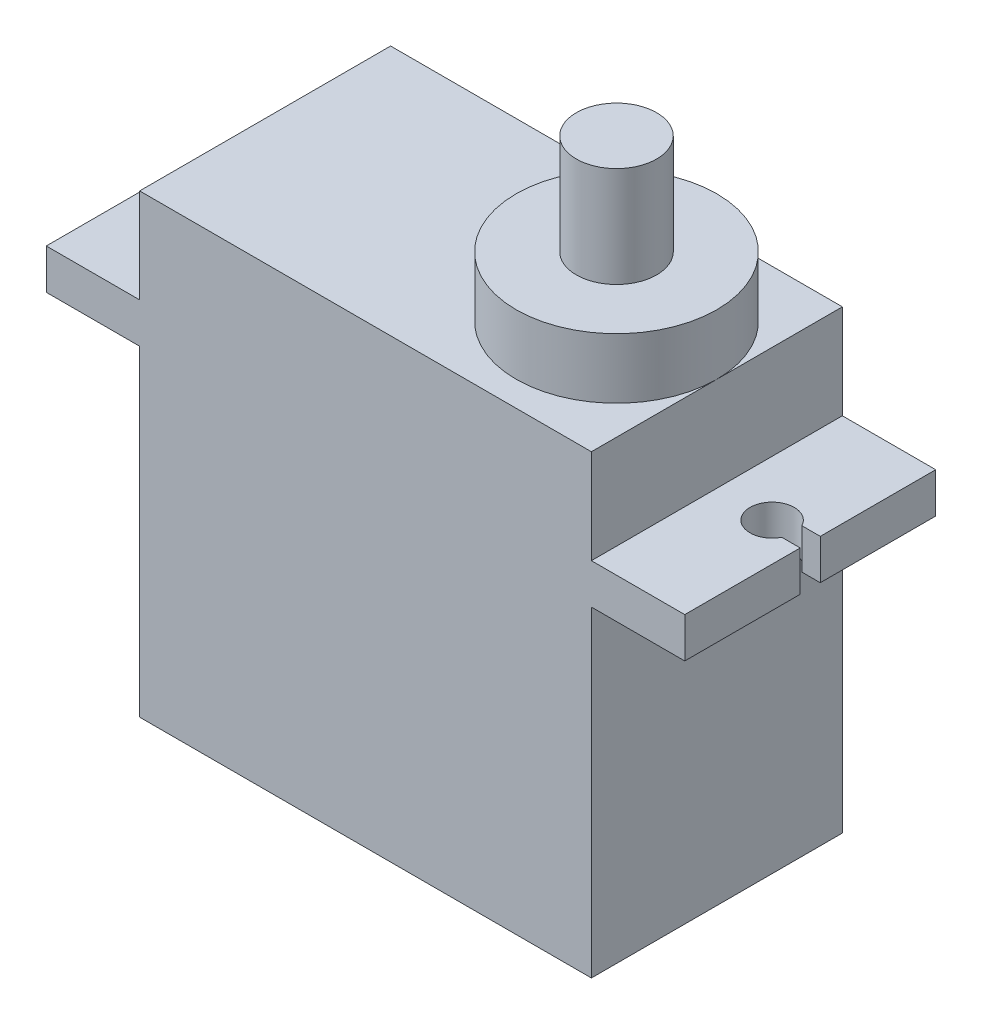
SolidWorks part; units mm, degrees
ref_plane "前视基准面" through (0, 0, 0) normal (0, 0, 1) x (1, 0, 0)
ref_plane "上视基准面" through (0, 0, 0) normal (0, 1, 0) x (1, 0, 0)
ref_plane "右视基准面" through (0, 0, 0) normal (1, 0, 0) x (0, 0, -1)
sketch "草图1" plane through (0, 0, 0) normal (0, 1, 0) x (1, 0, 0)
  line L1 (-11.25, 6.25) -> (11.25, 6.25)
  line L2 (-11.25, 6.25) -> (-11.25, -6.25)
  line L3 (-11.25, -6.25) -> (11.25, -6.25)
  line L4 (11.25, 6.25) -> (11.25, -6.25)
  line L5 (-11.25, 6.25) -> (11.25, -6.25) construction
  line L6 (-11.25, -6.25) -> (11.25, 6.25) construction
  point P0 (0, 0)
  dimension "D1" = 22.5
  dimension "D2" = 12.5
extrude "凸台-拉伸1" add sketch "草图1" along normal blind 16
sketch "草图2" plane through (0, 16, 0) normal (0, 1, 0) x (1, 0, 0)
  line L0 (-11.25, -6.25) -> (11.25, -6.25) construction
  line L1 (-15.9, 6.25) -> (15.9, 6.25)
  line L2 (-15.9, 6.25) -> (-15.9, 0.5)
  line L3 (-15.9, -6.25) -> (15.9, -6.25)
  line L4 (15.9, 6.25) -> (15.9, 0.5)
  line L5 (-15.9, 6.25) -> (15.9, -6.25) construction
  line L6 (-15.9, -6.25) -> (15.9, 6.25) construction
  line L7 (-15.9, 0.5) -> (-14.9798, 0.5)
  line L8 (-14, 0) -> (0, 0) construction
  line L9 (-15.9, -0.5) -> (-14.9798, -0.5)
  line L10 (-15.9, -0.5) -> (-15.9, -6.25)
  line L11 (0, 0) -> (0, 10.833) construction
  line L12 (15.9, -0.5) -> (14.9798, -0.5)
  line L13 (15.9, 0.5) -> (14.9798, 0.5)
  line L14 (15.9, -0.5) -> (15.9, -6.25)
  arc A0 (-14.9798, -0.5) -> (-14.9798, 0.5) centre (-14, 0) ccw
  arc A1 (14.9798, -0.5) -> (14.9798, 0.5) centre (14, 0) cw
  point P0 (0, 0)
  dimension "D2" = 2.2
  dimension "D3" = 28
  dimension "D1" = 31.8
  dimension "D4" = 1
extrude "凸台-拉伸2" add sketch "草图2" along normal blind 2
sketch "草图3" plane through (0, 18, 0) normal (0, 1, 0) x (1, 0, 0)
  line L4 (11.25, -6.25) -> (11.25, 6.25)
  line L5 (-11.25, -6.25) -> (11.25, -6.25)
  line L6 (-11.25, 6.25) -> (-11.25, -6.25)
  line L7 (11.25, 6.25) -> (-11.25, 6.25)
  line L8 (11.25, -6.25) -> (11.25, 6.25)
  line L9 (-11.25, -6.25) -> (11.25, -6.25)
  line L10 (-11.25, 6.25) -> (-11.25, -6.25)
  line L11 (11.25, 6.25) -> (-11.25, 6.25)
  dimension "D1" = 0
extrude "凸台-拉伸3" add sketch "草图3" along normal blind 4.7
sketch "草图4" plane through (0, 22.7, 0) normal (0, 1, 0) x (1, 0, 0)
  line L0 (0, 0) -> (18.4313, 0) construction
  line L1 (11.25, -6.25) -> (11.25, 6.25) construction
  circle A0 centre (6.25, 0) radius 5
  dimension "D1" = 5
extrude "凸台-拉伸4" add sketch "草图4" along normal blind 3
sketch "草图5" plane through (0, 25.7, 0) normal (0, 1, 0) x (1, 0, 0)
  circle A0 centre (6.25, 0) radius 2
  dimension "D1" = 4
extrude "凸台-拉伸5" add sketch "草图5" along normal blind 5
